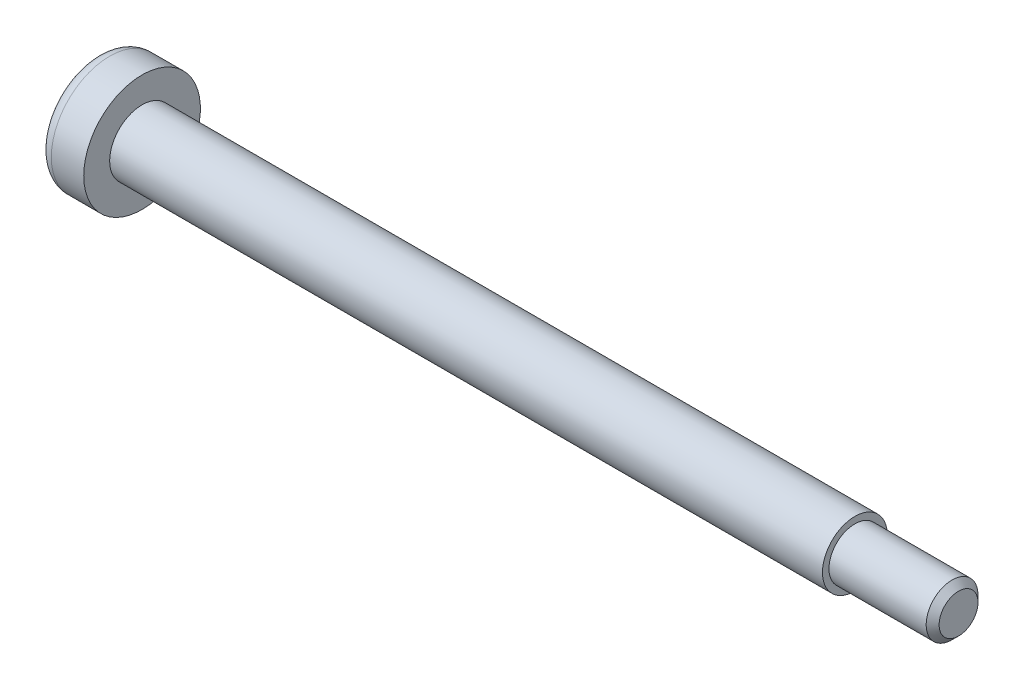
SolidWorks part; units mm, degrees
material "不锈钢 (铁素体)"
ref_plane "前视基准面" through (0, 0, 0) normal (0, 0, 1) x (1, 0, 0)
ref_plane "上视基准面" through (0, 0, 0) normal (0, 1, 0) x (1, 0, 0)
ref_plane "右视基准面" through (0, 0, 0) normal (1, 0, 0) x (0, 0, -1)
sketch "草图1" plane through (0, 0, 0) normal (0, 0, 1) x (1, 0, 0)
  line L0 (0, 0) -> (66.5, 0) construction
  line L1 (0, 0) -> (0, 4.5)
  line L2 (0, 4.5) -> (3.5, 4.5)
  line L3 (3.5, 4.5) -> (3.5, 2.5)
  line L4 (3.5, 2.5) -> (58.5, 2.5)
  line L5 (58.5, 2.5) -> (58.5, 2)
  line L6 (58.5, 2) -> (66.5, 2)
  line L7 (66.5, 2) -> (66.5, 0)
  line L8 (0, 0) -> (66.5, 0)
  dimension "D1" = 9
  dimension "D2" = 5
  dimension "D3" = 4
  dimension "D4" = 8
  dimension "D5" = 3.5
  dimension "D6" = 55
revolve "旋转1" add sketch "草图1" angle 360 about L0
cosmetic thread "装饰螺纹线1" parameters "D2"=3.242
sketch "草图2" plane through (0, 0, 0) normal (-1, 0, 0) x (0, 0, 1)
  line L0 (0, 0) -> (0, 1.7321) construction
  line L1 (0, 1.7321) -> (-1.5, 0.866)
  line L2 (-1.5, 0.866) -> (-1.5, -0.866)
  line L3 (-1.5, -0.866) -> (0, -1.7321)
  line L4 (0, -1.7321) -> (1.5, -0.866)
  line L5 (1.5, -0.866) -> (1.5, 0.866)
  line L6 (1.5, 0.866) -> (0, 1.7321)
  circle A0 centre (0, 0) radius 1.5 construction
  dimension "D1" = 3
extrude "切除-拉伸1" cut sketch "草图2" against normal blind 2.4
fillet "圆角1" radius 1 1 edges at (0, 0, 4.5)
chamfer "倒角1" distance 0.5 angle 45 1 edges at (66.5, 0, 2)
